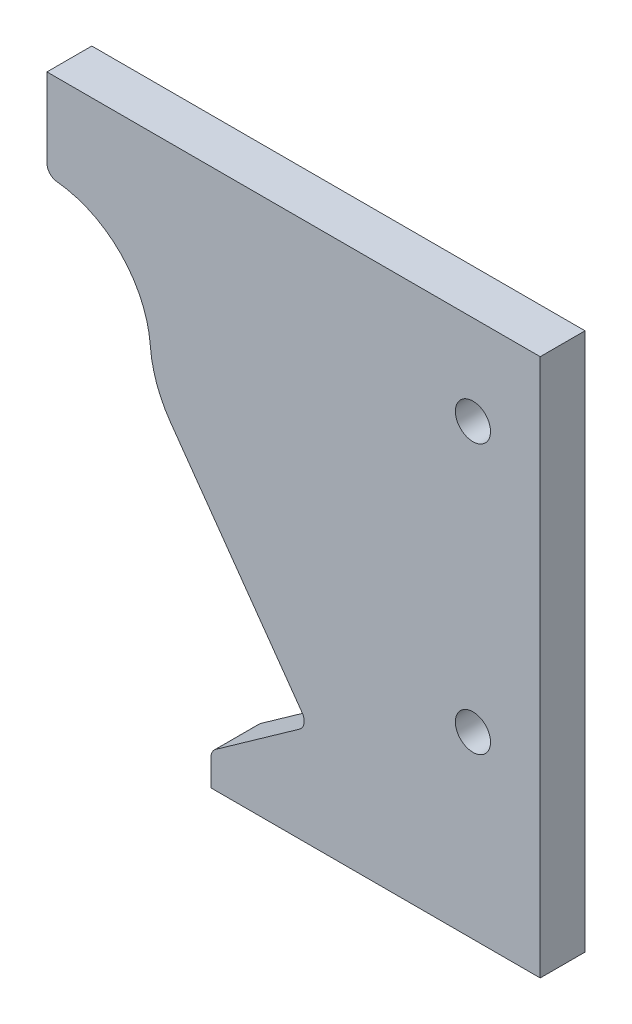
SolidWorks part; units mm, degrees
material "6061 Alloy"
ref_plane "X-Y Datum" through (0, 0, 0) normal (0, 0, 1) x (1, 0, 0)
ref_plane "X-Z Datum" through (0, 0, 0) normal (0, 1, 0) x (1, 0, 0)
ref_plane "Y-Z Datum" through (0, 0, 0) normal (1, 0, 0) x (0, 0, -1)
sketch "Sketch1" plane through (0, 0, 0) normal (0, 0, 1) x (1, 0, 0)
  line L23 (23.2296, -44.2283) -> (37.0529, -34.43)
  line L24 (37.0529, -34.43) -> (17.5173, -6.8694)
  line L41 (0, 14.6812) -> (0, 27.3812)
  line L42 (0, 27.3812) -> (69.85, 27.3812)
  line L43 (69.85, 27.3812) -> (69.85, -48.8188)
  line L44 (69.85, -48.8188) -> (23.2296, -48.8188)
  line L45 (23.2296, -48.8188) -> (23.2296, -44.2283)
  arc A14 (14.6392, 1.1103) -> (0, 14.6812) centre (0, 0) ccw
  arc A15 (17.5173, -6.8694) -> (14.6392, 1.1103) centre (30.4687, 2.3108) cw
  circle A17 centre (60.325, 14.6812) radius 2.4892
  circle A18 centre (60.325, -23.4188) radius 2.4892
  dimension "D4" = 15.875
  dimension "D8" = 14.6812
  dimension "D11" = 69.85
  dimension "D13" = 25.4
  dimension "D7" = 4.9784
  dimension "D2" = 14.6392
  dimension "D3" = 17.5173
  dimension "D5" = 23.2296
  dimension "D6" = 37.0529
  dimension "D9" = 9.525
  dimension "D10" = 12.7
  dimension "D12" = 76.2
  dimension "D14" = 12.7
extrude "Boss-Extrude1" add sketch "Sketch1" along normal mid plane 6.35
fillet "Fillet1" radius 1.5875 3 edges at (0, 14.6812, 0) (23.2296, -44.2283, 0) (37.0529, -34.43, 0)
